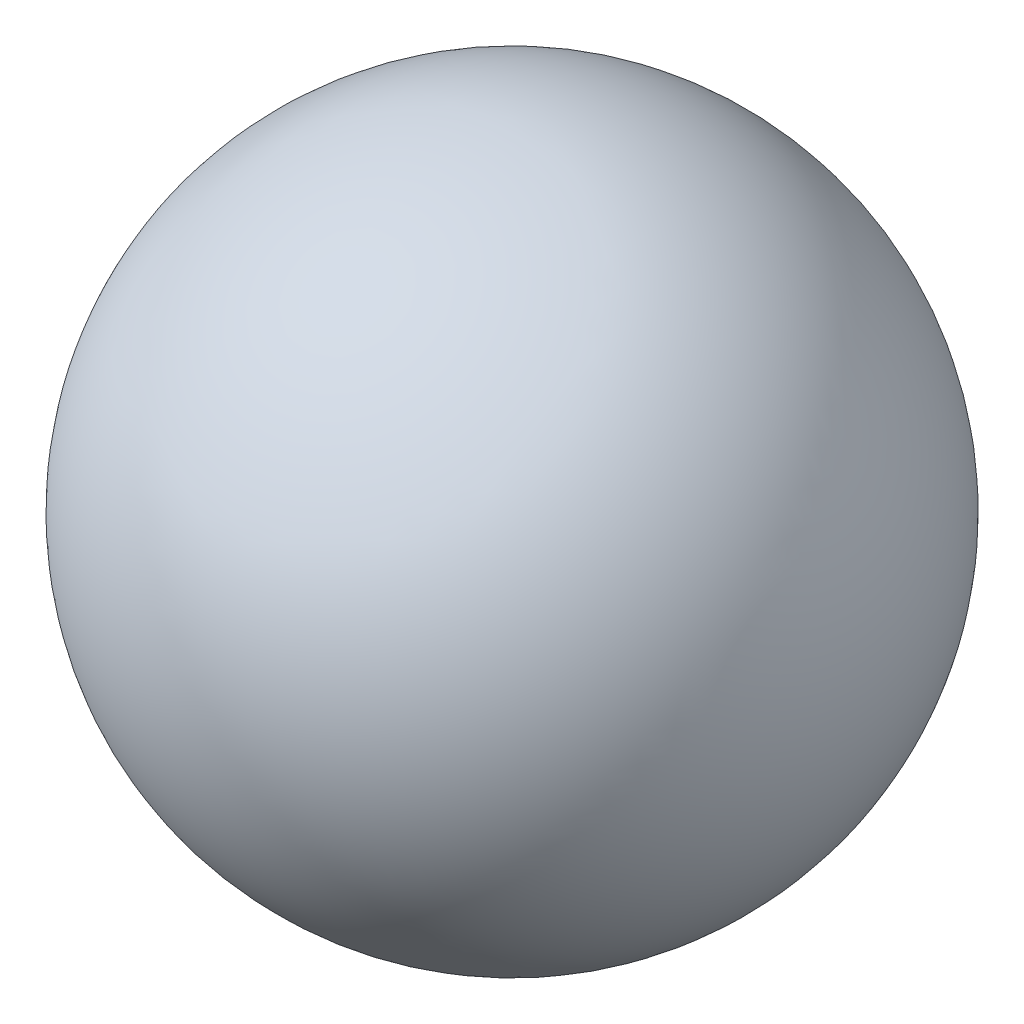
SolidWorks part; units mm, degrees
ref_plane "Plan1" through (0, 0, 0) normal (0, 0, 1) x (1, 0, 0)
ref_plane "Plan2" through (0, 0, 0) normal (0, 1, 0) x (1, 0, 0)
ref_plane "Plan3" through (0, 0, 0) normal (1, 0, 0) x (0, 0, -1)
sketch "Esquisse1" plane through (0, 0, 0) normal (0, 0, 1) x (1, 0, 0)
  line L0 (4.8879, 22.5) -> (-5.0679, 22.5) construction
  line L1 (-2.8571, 22.5) -> (2.8571, 22.5)
  arc A0 (2.8571, 22.5) -> (-2.8571, 22.5) centre (0, 22.5) ccw
  dimension "D1" = 2.8571
revolve "Base-Révolution" add sketch "Esquisse1" angle 360 about L0
